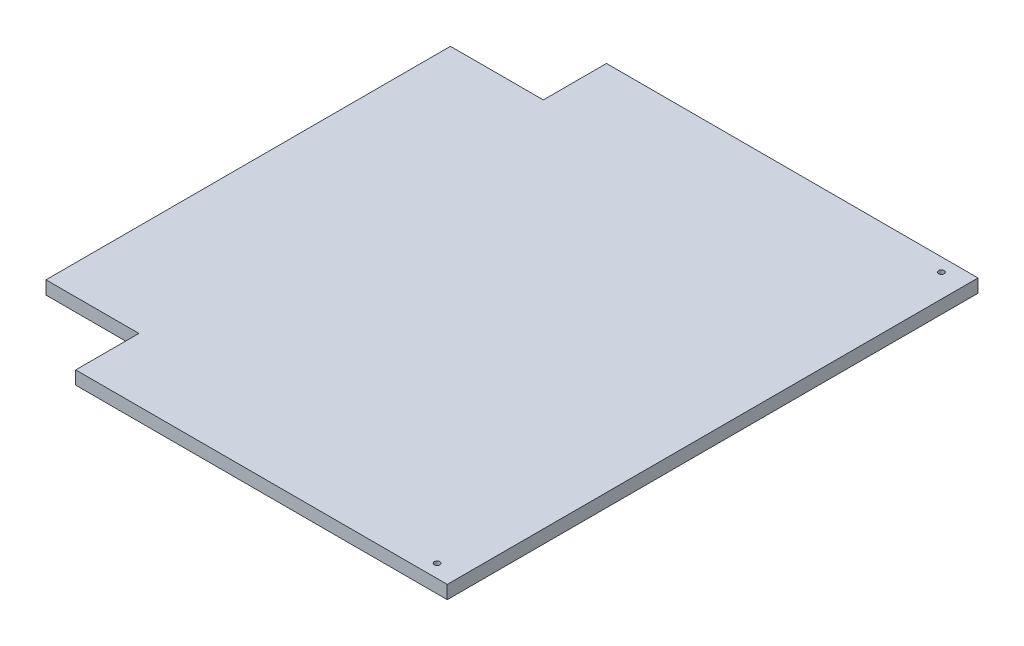
SolidWorks part; units mm, degrees
ref_plane "Front Plane" through (0, 0, 0) normal (0, 0, 1) x (1, 0, 0)
ref_plane "Top Plane" through (0, 0, 0) normal (0, 1, 0) x (1, 0, 0)
ref_plane "Right Plane" through (0, 0, 0) normal (1, 0, 0) x (0, 0, -1)
sketch "Sketch1" plane through (0, 0, 0) normal (0, 1, 0) x (1, 0, 0)
  line L0 (-222.25, 254) -> (222.25, -254) construction
  line L1 (-222.25, 254) -> (222.25, 254)
  line L2 (-222.25, 254) -> (-222.25, -254)
  line L3 (-222.25, -254) -> (222.25, -254)
  line L4 (222.25, 254) -> (222.25, -254)
  dimension "D1" = 508
  dimension "D2" = 444.5
extrude "Boss-Extrude1" add sketch "Sketch1" along normal mid plane 12.7
sketch "Sketch2" plane through (0, 6.35, 0) normal (0, 1, 0) x (1, 0, 0)
  line L10 (222.25, 254) -> (-222.25, 254) construction
  line L11 (-222.25, 254) -> (-133.35, 254)
  line L12 (-222.25, 254) -> (-222.25, 193.548)
  line L13 (-222.25, 193.548) -> (-133.35, 193.548)
  line L14 (-133.35, 254) -> (-133.35, 193.548)
  line L15 (-222.25, 254) -> (-222.25, -254) construction
  dimension "D2" = 88.9
  dimension "D8" = 60.452
extrude "Cut-Extrude1" cut sketch "Sketch2" against normal blind 230.886
mirror "Mirror1" about plane through (0, 0, 0) normal (0, 0, 1) of "Cut-Extrude1"
sketch "Sketch3" plane through (0, 6.35, 0) normal (0, 1, 0) x (1, 0, 0)
  line L0 (-133.35, -254) -> (222.25, -254) construction
  line L1 (222.25, 254) -> (-133.35, 254) construction
  line L2 (222.25, -254) -> (222.25, 254) construction
  line L3 (222.25, -254) -> (222.25, 254) construction
  circle A0 centre (199.898, -241.3) radius 2.667
  circle A20 centre (199.898, 241.3) radius 2.667
  dimension "D1" = 12.7
  dimension "D2" = 12.7
  dimension "D3" = 5.334
  dimension "D4" = 22.352
  dimension "D5" = 22.352
extrude "Cut-Extrude2" cut sketch "Sketch3" against normal blind 230.886
